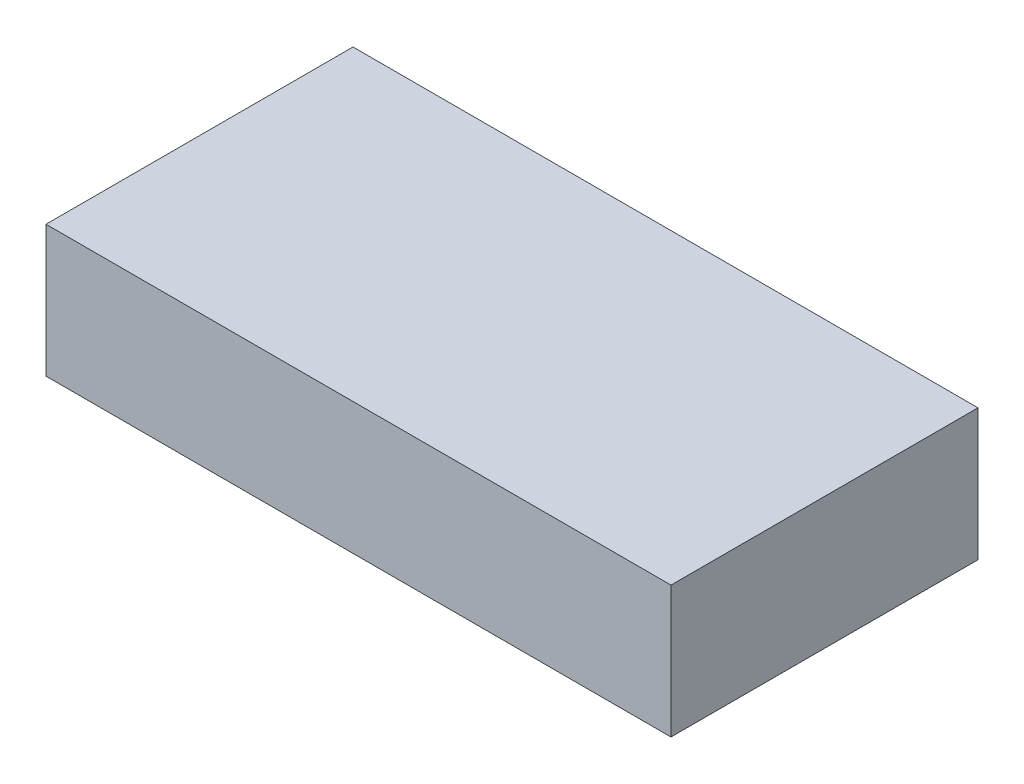
SolidWorks part; units mm, degrees
material "Pine"
ref_plane "Front Plane" through (0, 0, 0) normal (0, 0, 1) x (1, 0, 0)
ref_plane "Top Plane" through (0, 0, 0) normal (0, 1, 0) x (1, 0, 0)
ref_plane "Right Plane" through (0, 0, 0) normal (1, 0, 0) x (0, 0, -1)
sketch "Sketch1" plane through (0, 0, 0) normal (1, 0, 0) x (0, 0, -1)
  line L1 (-44.45, -19.05) -> (44.45, -19.05)
  line L2 (-44.45, -19.05) -> (-44.45, 19.05)
  line L3 (-44.45, 19.05) -> (44.45, 19.05)
  line L4 (44.45, -19.05) -> (44.45, 19.05)
  line L5 (-44.45, -19.05) -> (44.45, 19.05) construction
  line L6 (-44.45, 19.05) -> (44.45, -19.05) construction
  point P0 (0, 0)
  dimension "D1" = 38.1
  dimension "D2" = 88.9
extrude "Boss-Extrude1" add sketch "Sketch1" along normal mid plane 180.975
